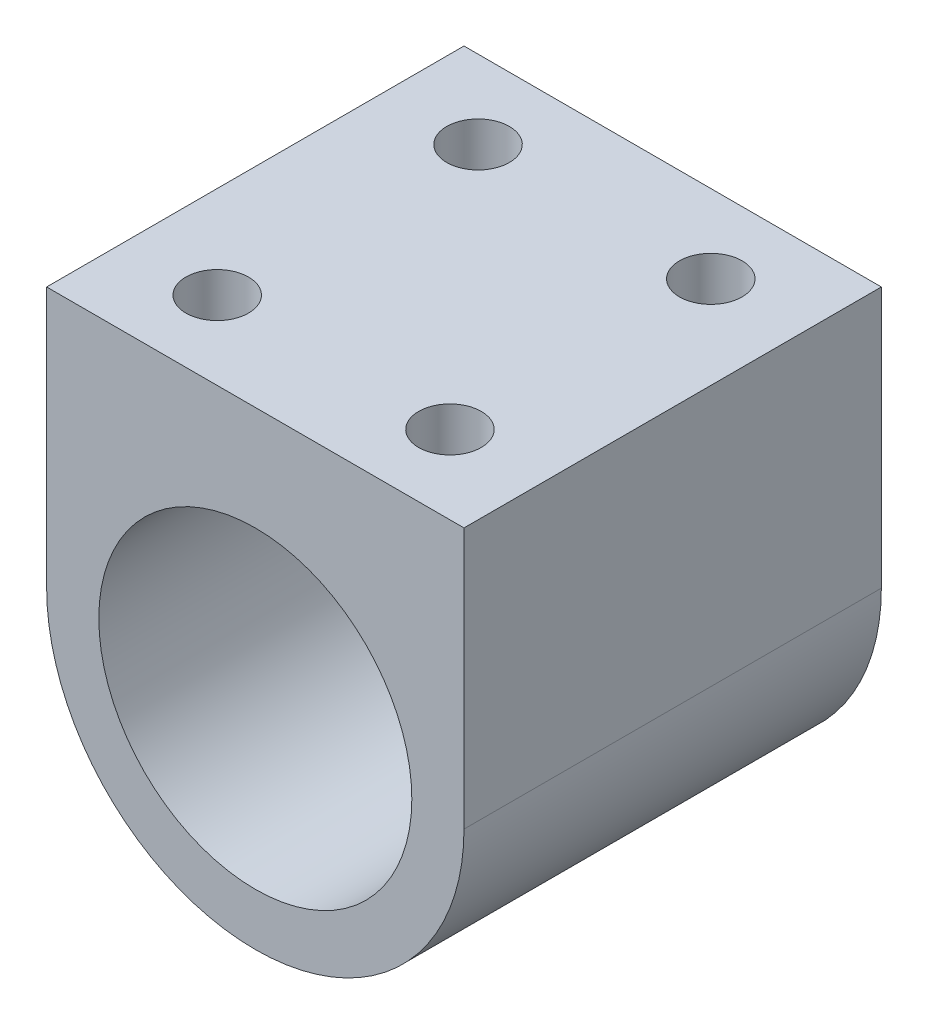
SolidWorks part; units mm, degrees
ref_plane "前视基准面" through (0, 0, 0) normal (0, 0, 1) x (1, 0, 0)
ref_plane "上视基准面" through (0, 0, 0) normal (0, 1, 0) x (1, 0, 0)
ref_plane "右视基准面" through (0, 0, 0) normal (1, 0, 0) x (0, 0, -1)
sketch "草图1" plane through (0, 0, 0) normal (0, 0, 1) x (1, 0, 0)
  line L0 (0, 20) -> (0, 26.3477) construction
  line L1 (20, 25) -> (-20, 25)
  line L2 (0, 0) -> (-15, 0) construction
  line L3 (-20, 25) -> (-20, 0)
  line L4 (20, 25) -> (20, 0)
  arc A1 (-20, 0) -> (20, 0) centre (0, 0) ccw
  point P7 (0, 25)
  dimension "D2" = 20
  dimension "D3" = 25
extrude "凸台-拉伸1" add sketch "草图1" along normal blind 40
sketch "草图2" plane through (0, 0, 40) normal (0, 0, 1) x (1, 0, 0)
  circle A0 centre (0, 0) radius 15
  dimension "D1" = 30
extrude "切除-拉伸1" cut sketch "草图2" against normal blind 35
sketch "草图3" plane through (0, 25, 0) normal (0, 1, 0) x (1, 0, 0)
  line L0 (0, 0) -> (0, -40) construction
  line L1 (20, -40) -> (-20, -40) construction
  line L2 (20, 0) -> (-20, 0) construction
  circle A0 centre (11.154, -7.5) radius 3
  circle A1 centre (-11.154, -7.5) radius 3
  circle A2 centre (11.154, -32.5) radius 3
  circle A3 centre (-11.154, -32.5) radius 3
  dimension "D1" = 6
  dimension "D2" = 7.5
  dimension "D3" = 2
extrude "切除-拉伸2" cut sketch "草图3" against normal blind 12
